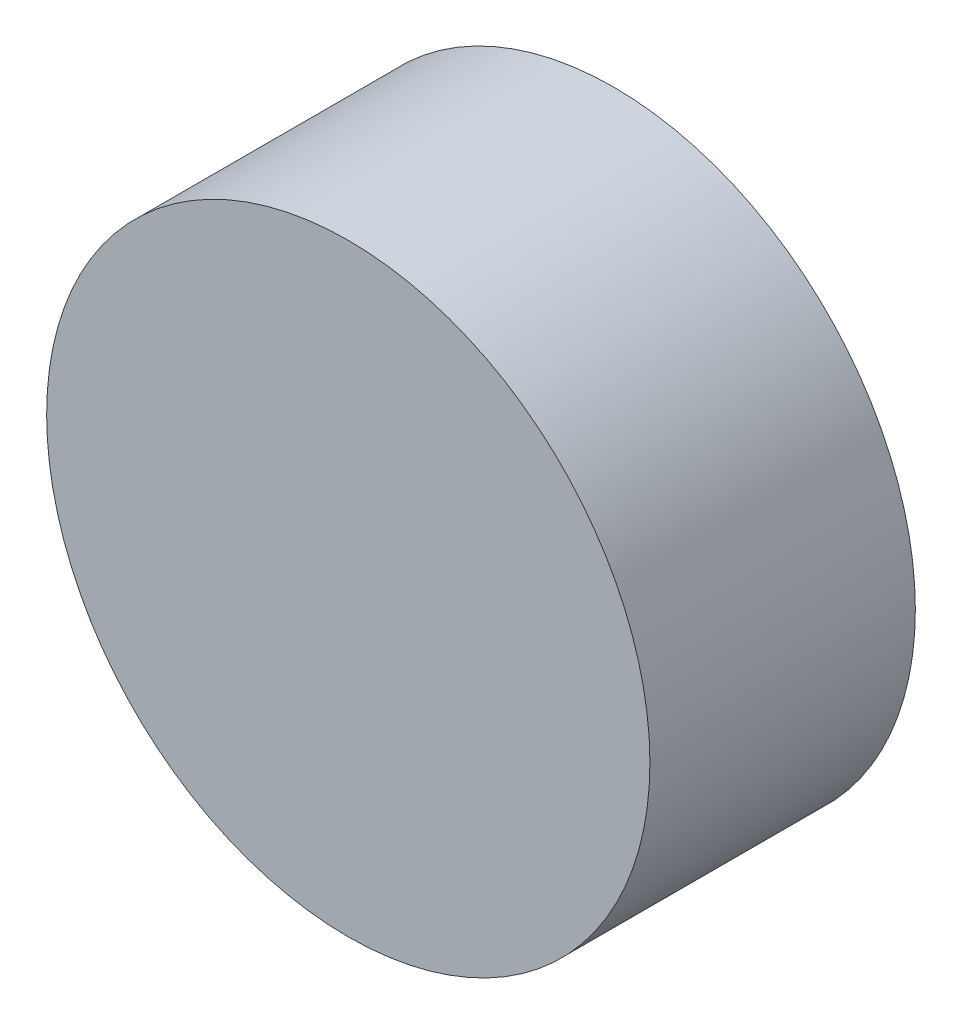
SolidWorks part; units mm, degrees
ref_plane "前视基准面" through (0, 0, 0) normal (0, 0, 1) x (1, 0, 0)
ref_plane "上视基准面" through (0, 0, 0) normal (0, 1, 0) x (1, 0, 0)
ref_plane "右视基准面" through (0, 0, 0) normal (1, 0, 0) x (0, 0, -1)
sketch "草图1" plane through (0, 0, 0) normal (0, 0, 1) x (1, 0, 0)
  circle A0 centre (0, 0) radius 12.5
  dimension "D1" = 25
extrude "凸台-拉伸1" add sketch "草图1" along normal blind 11
